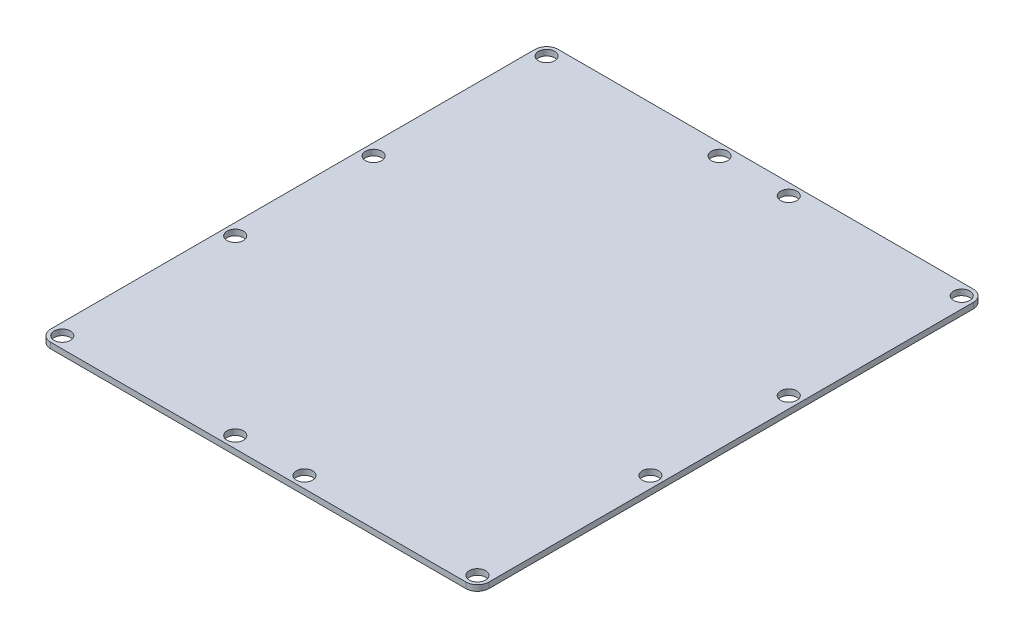
SolidWorks part; units mm, degrees
ref_plane "Front Plane" through (0, 0, 0) normal (0, 0, 1) x (1, 0, 0)
ref_plane "Top Plane" through (0, 0, 0) normal (0, 1, 0) x (1, 0, 0)
ref_plane "Right Plane" through (0, 0, 0) normal (1, 0, 0) x (0, 0, -1)
sketch "Sketch1" plane through (0, 0, 0) normal (0, 1, 0) x (1, 0, 0)
  line L1 (60.325, -69.85) -> (-60.325, -69.85)
  line L2 (60.325, -69.85) -> (60.325, 69.85)
  line L3 (60.325, 69.85) -> (-60.325, 69.85)
  line L4 (-60.325, -69.85) -> (-60.325, 69.85)
  line L5 (60.325, -69.85) -> (-60.325, 69.85) construction
  line L6 (60.325, 69.85) -> (-60.325, -69.85) construction
  point P0 (0, 0)
  dimension "D1" = 120.65
  dimension "D2" = 139.7
extrude "Boss-Extrude1" add sketch "Sketch1" along normal blind 1.5875
sketch "Sketch2" plane through (0, 1.5875, 0) normal (0, 1, 0) x (1, 0, 0)
  line L8 (-60.325, 69.85) -> (-60.325, -69.85) construction
  line L9 (60.325, -69.85) -> (60.325, 69.85) construction
  line L10 (60.325, 69.85) -> (-60.325, 69.85) construction
  line L11 (-60.325, -69.85) -> (60.325, -69.85) construction
  line L12 (-57.15, 66.675) -> (-57.15, -66.675)
  line L13 (-57.15, -66.675) -> (57.15, -66.675)
  line L14 (57.15, -66.675) -> (57.15, 66.675)
  line L15 (57.15, 66.675) -> (-57.15, 66.675)
  line L16 (-57.15, 66.675) -> (-57.15, -66.675) construction
  line L17 (-57.15, -66.675) -> (57.15, -66.675) construction
  line L18 (57.15, -66.675) -> (57.15, 66.675) construction
  line L19 (57.15, 66.675) -> (-57.15, 66.675) construction
  point P0 (-57.15, 19.05)
  point P1 (-57.15, -19.05)
  point P2 (57.15, -19.05)
  point P3 (57.15, 19.05)
  point P4 (9.525, 66.675)
  point P5 (-9.525, 66.675)
  point P7 (-9.525, -66.675)
  point P9 (9.525, -66.675)
  dimension "D2" = 50.8
  dimension "D3" = 50.8
  dimension "D4" = 50.8
  dimension "D5" = 50.8
  dimension "D1" = 3.175
hole_wizard "#8 Clearance Hole1" positions "Sketch3" profile "Sketch4" hole size "#8" standard "ANSI Inch" end condition up to next
sketch "Sketch3" plane through (0, 1.5875, 0) normal (0, 1, 0) x (1, 0, 0)
  point P0 (-57.15, 66.675)
  point P3 (-57.15, 19.05)
  point P6 (-57.15, -19.05)
  point P9 (-57.15, -66.675)
  point P12 (-9.525, -66.675)
  point P15 (9.525, -66.675)
  point P18 (57.15, -66.675)
  point P21 (57.15, -19.05)
  point P24 (57.15, 19.05)
  point P27 (57.15, 66.675)
  point P30 (9.525, 66.675)
  point P33 (-9.525, 66.675)
sketch "Sketch4" plane through (-57.15, 1.5875, -66.675) normal (1, 0, 0) x (0, 0, 1)
  line L0 (0, 0) -> (0, 1.5875)
  line L1 (0, 1.5875) -> (2.2479, 1.5875)
  line L2 (2.2479, 1.5875) -> (2.2479, 0)
  line L5 (2.2479, 0) -> (0, 0)
  line L11 (0, -6.35) -> (0, 107.95) construction
  dimension "Thru Hole Dia." = 4.4958
  dimension "Thru Hole Depth" = 1.5875
fillet "Fillet1" radius 3.175 4 edges at (60.325, 0.7937, 69.85) (-60.325, 0.7937, 69.85) (-60.325, 0.7937, -69.85) (60.325, 0.7937, -69.85)
